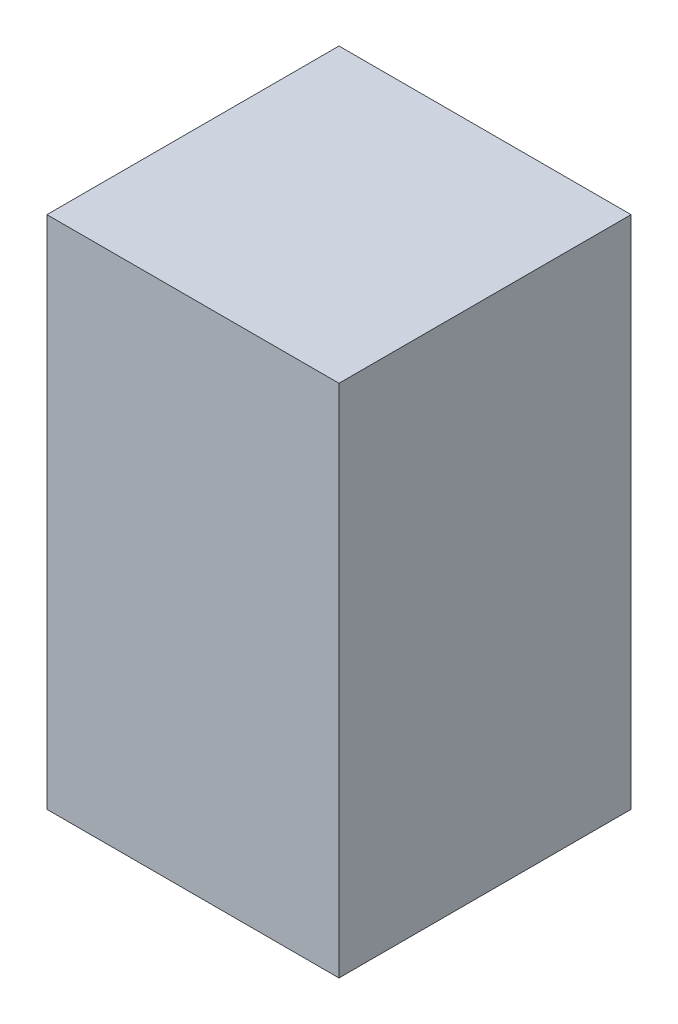
SolidWorks part; units mm, degrees
ref_plane "Front" through (0, 0, 0) normal (0, 0, 1) x (1, 0, 0)
ref_plane "Top" through (0, 0, 0) normal (0, 1, 0) x (1, 0, 0)
ref_plane "Right" through (0, 0, 0) normal (1, 0, 0) x (0, 0, -1)
sketch "Sketch1" plane through (0, 0, 0) normal (0, 1, 0) x (1, 0, 0)
  line L1 (-609.6, -609.6) -> (609.6, -609.6)
  line L2 (-609.6, -609.6) -> (-609.6, 609.6)
  line L3 (-609.6, 609.6) -> (609.6, 609.6)
  line L4 (609.6, -609.6) -> (609.6, 609.6)
  line L5 (-609.6, -609.6) -> (609.6, 609.6) construction
  line L6 (-609.6, 609.6) -> (609.6, -609.6) construction
  point P0 (0, 0)
  dimension "D1" = 1219.2
extrude "Boss-Extrude1" add sketch "Sketch1" along normal blind 2150
